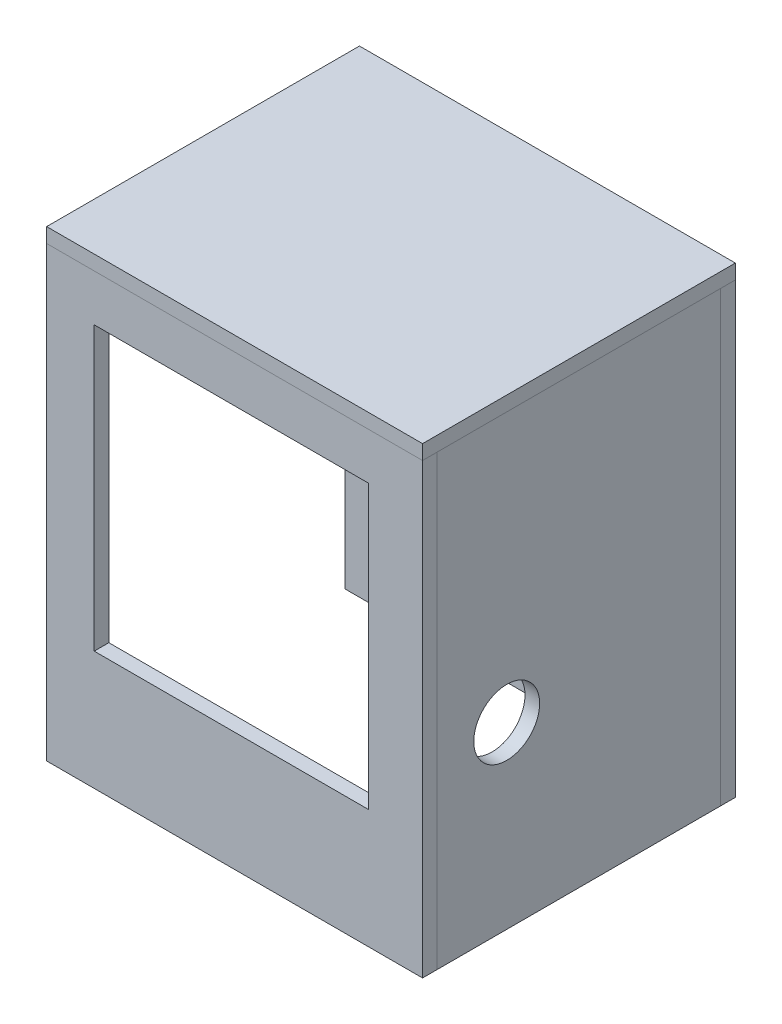
SolidWorks part; units mm, degrees
material "Polyurethane Foam Rigid"
ref_plane "Front Plane" through (0, 0, 0) normal (0, 0, 1) x (1, 0, 0)
ref_plane "Top Plane" through (0, 0, 0) normal (0, 1, 0) x (1, 0, 0)
ref_plane "Right Plane" through (0, 0, 0) normal (1, 0, 0) x (0, 0, -1)
sketch "Sketch1" plane through (0, 0, 0) normal (0, 0, 1) x (1, 0, 0)
  line L1 (0, 0) -> (658.8125, 0)
  line L2 (0, 0) -> (0, 777.875)
  line L3 (0, 777.875) -> (658.8125, 777.875)
  line L4 (658.8125, 0) -> (658.8125, 777.875)
  dimension "D1" = 777.875
  dimension "D2" = 658.8125
extrude "Boss-Extrude1" add sketch "Sketch1" along normal blind 25.4
sketch "Sketch2" plane through (0, 0, 0) normal (0, 0, -1) x (-1, 0, 0)
  line L0 (-658.8125, 777.875) -> (0, 777.875) construction
  line L1 (-658.8125, 0) -> (-633.4125, 0)
  line L2 (-658.8125, 0) -> (-658.8125, 777.875)
  line L3 (-658.8125, 777.875) -> (-633.4125, 777.875)
  line L4 (-633.4125, 0) -> (-633.4125, 777.875)
  dimension "D1" = 25.4
extrude "Boss-Extrude2" add sketch "Sketch2" along normal blind 492.125 separate body
sketch "Sketch3" plane through (0, 0, -492.125) normal (0, 0, -1) x (-1, 0, 0)
  line L1 (-658.8125, 777.875) -> (0, 777.875)
  line L2 (-658.8125, 777.875) -> (-658.8125, 0)
  line L3 (-658.8125, 0) -> (0, 0)
  line L4 (0, 777.875) -> (0, 0)
  dimension "D1" = 658.8125
  dimension "D2" = 777.875
extrude "Boss-Extrude3" add sketch "Sketch3" along normal blind 25.4 separate body
sketch "Sketch4" plane through (0, 777.875, 0) normal (0, 1, 0) x (1, 0, 0)
  line L1 (658.8125, -25.4) -> (0, -25.4)
  line L2 (658.8125, -25.4) -> (658.8125, 517.525)
  line L3 (658.8125, 517.525) -> (0, 517.525)
  line L4 (0, -25.4) -> (0, 517.525)
extrude "Boss-Extrude4" add sketch "Sketch4" along normal blind 25.4 separate body
sketch "Sketch5" plane through (0, 0, 0) normal (-1, 0, 0) x (0, 0, 1)
  line L1 (-517.525, 803.275) -> (25.4, 803.275)
  line L2 (-517.525, 803.275) -> (-517.525, 0)
  line L3 (-517.525, 0) -> (25.4, 0)
  line L4 (25.4, 803.275) -> (25.4, 0)
extrude "Cut-Extrude1" cut sketch "Sketch5" against normal blind 6.35
sketch "Sketch6" plane through (0, 0, 25.4) normal (0, 0, 1) x (1, 0, 0)
  line L0 (6.35, 0) -> (6.35, 777.875) construction
  line L1 (88.9, 696.9125) -> (565.15, 696.9125)
  line L2 (88.9, 696.9125) -> (88.9, 206.375)
  line L3 (88.9, 206.375) -> (565.15, 206.375)
  line L4 (565.15, 696.9125) -> (565.15, 206.375)
  line L5 (658.8125, 0) -> (658.8125, 777.875) construction
  line L6 (6.35, 803.275) -> (658.8125, 803.275) construction
  line L7 (6.35, 0) -> (658.8125, 0) construction
  dimension "D1" = 82.55
  dimension "D2" = 93.6625
  dimension "D3" = 106.3625
  dimension "D4" = 206.375
extrude "Cut-Extrude2" cut sketch "Sketch6" against normal up to next (25.4 mm away)
sketch "Sketch7" plane through (658.8125, 0, 0) normal (1, 0, 0) x (0, 0, -1)
  circle A0 centre (120.65, 311.15) radius 57.15
extrude "Cut-Extrude3" cut sketch "Sketch7" against normal blind 25.4
